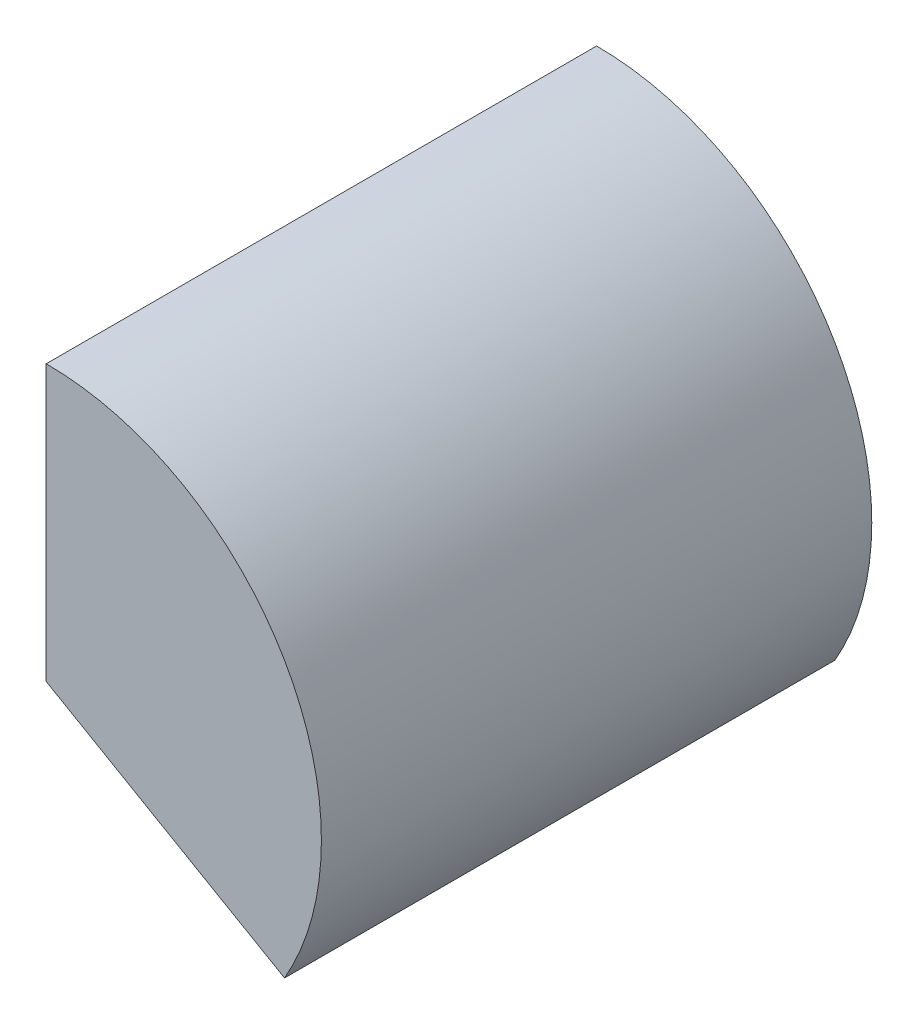
SolidWorks part; units mm, degrees
ref_plane "Alzado" through (0, 0, 0) normal (0, 0, 1) x (1, 0, 0)
ref_plane "Planta" through (0, 0, 0) normal (0, 1, 0) x (1, 0, 0)
ref_plane "Vista lateral" through (0, 0, 0) normal (1, 0, 0) x (0, 0, -1)
sketch "Croquis1" plane through (0, 0, 0) normal (0, 0, 1) x (1, 0, 0)
  line L0 (0, 25) -> (0, 0)
  line L1 (0, 0) -> (21.6506, -12.5)
  arc A0 (21.6506, -12.5) -> (0, 25) centre (0, 0) ccw
  dimension "D1" = 50
  dimension "D2" = 120
extrude "Saliente-Extruir1" add sketch "Croquis1" along normal blind 50
sketch "Croquis2" plane through (0, 0, 0) normal (0, 0, -1) x (-1, 0, 0)
  circle A0 centre (-11.9164, 5.554) radius 5
  dimension "D1" = 10
extrude "Cortar-Extruir1" cut sketch "Croquis2" against normal blind 10
